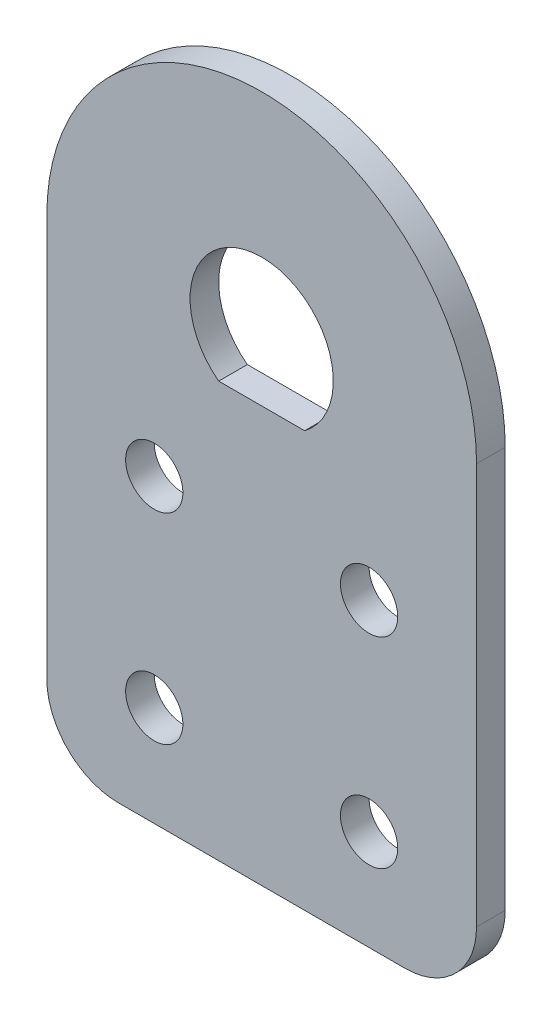
SolidWorks part; units mm, degrees
material "轻木"
ref_plane "前视基准面" through (0, 0, 0) normal (0, 0, 1) x (1, 0, 0)
ref_plane "上视基准面" through (0, 0, 0) normal (0, 1, 0) x (1, 0, 0)
ref_plane "右视基准面" through (0, 0, 0) normal (1, 0, 0) x (0, 0, -1)
sketch "草图1" plane through (0, 0, 0) normal (0, 0, 1) x (1, 0, 0)
  line L0 (0, -55) -> (0, 55) construction
  line L1 (15, 18.8035) -> (15, -14.1965)
  line L2 (15, -14.1965) -> (-15, -14.1965)
  line L3 (-15, -14.1965) -> (-15, 18.8035)
  line L5 (-3, 14.8035) -> (3, 14.8035)
  circle A0 centre (-7.5, 6.8035) radius 2
  circle A1 centre (-7.5, -7.1965) radius 2
  arc A4 (3, 14.8035) -> (-3, 14.8035) centre (0, 18.8035) ccw
  circle A5 centre (7.5, -7.1965) radius 2
  circle A6 centre (7.5, 6.8035) radius 2
  arc A7 (15, 18.8035) -> (-15, 18.8035) centre (0, 18.8035) ccw
  dimension "D2" = 12
  dimension "D3" = 33
  dimension "D1" = 14
extrude "凸台-拉伸1" add sketch "草图1" along normal blind 2
fillet "圆角1" radius 5 2 edges at (15, -14.1965, 1) (-15, -14.1965, 1)
